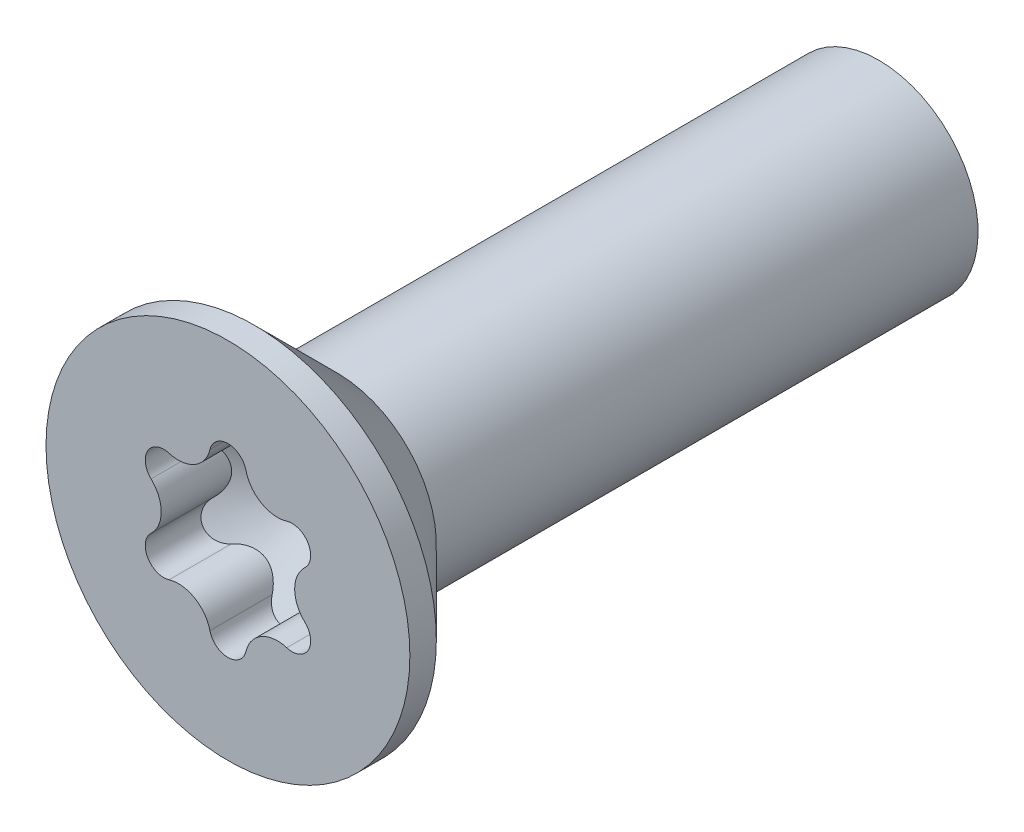
SolidWorks part; units mm, degrees
ref_plane "Front Plane" through (0, 0, 0) normal (0, 0, 1) x (1, 0, 0)
ref_plane "Top Plane" through (0, 0, 0) normal (0, 1, 0) x (1, 0, 0)
ref_plane "Right Plane" through (0, 0, 0) normal (1, 0, 0) x (0, 0, -1)
other "Configuration Table"
sketch "BodySke" plane through (0, 0, 0) normal (1, 0, 0) x (0, 0, -1)
  line L0 (0, 0) -> (-1787.2758, 0) construction
  line L1 (0, 0) -> (0, 2.75)
  line L2 (0.4, 2.75) -> (1.65, 1.5)
  line L3 (0.4, -2.75) -> (1.65, -1.5) construction
  line L4 (1.65, 1.5) -> (10, 1.5)
  line L5 (10, 1.5) -> (10, 0)
  line L6 (10, 0) -> (0, 0)
  line L7 (0, 0) -> (0, 50000) construction
  line L8 (0.4, 2.75) -> (0, 2.75)
  dimension "D" = 3
  dimension "Dk" = 5.5
  dimension "K" = 1.65
  dimension "L" = 10
  dimension "D1" = 90
  dimension "B" = 10
revolve "Base-Revolve" add sketch "BodySke" angle 360 about L0
cosmetic thread "ThreadCosmetic" [suppressed] parameters "ThdLen"=8.35, "MinorDia"=2.439
sketch "PreBSke" plane through (0, 0, 0) normal (1, 0, 0) x (0, 0, -1)
  line L0 (0, 0) -> (-50000, 0) construction
  line L1 (0, 0) -> (0, 1.4)
  line L2 (0, 3.15) -> (0, -3.15) construction
  line L3 (0, 1.4) -> (0.83, 1.4)
  line L4 (0.83, 1.4) -> (1.6712, 0)
  line L5 (1.6712, 0) -> (0, 0)
  line L6 (0.83, -1.4) -> (1.6712, 0) construction
  dimension "T" = 0.83
  dimension "A" = 2.8
  dimension "D1" = 118
revolve "PreBroach" cut sketch "PreBSke" angle 360 about L0
sketch "HexSke" plane through (0, 0, 0) normal (0, 0, 1) x (1, 0, 0)
  line L0 (0, 0) -> (-43301.2702, 25000) construction
  line L1 (0, 0) -> (-43301.2702, -25000) construction
  line L2 (0, 0) -> (50000, 0) construction
  arc A0 (-1.1621, -0.3564) -> (-1.1621, 0.3564) centre (-1.4984, 0) ccw
  arc A1 (-1.2124, 0.7) -> (-1.1621, 0.3564) centre (-0.9699, 0.56) ccw
  arc A2 (-1.1621, -0.3564) -> (-1.2124, -0.7) centre (-0.9699, -0.56) ccw
  arc A3 (-0.8897, 0.8282) -> (-1.2124, 0.7) centre (-0.9699, 0.56) ccw
  circle A4 centre (0, 0) radius 1.0084 construction
  circle A5 centre (0, 0) radius 1.4 construction
  arc A6 (-0.8897, 0.8282) -> (-0.2724, 1.1846) centre (-0.7492, 1.2977) ccw
  arc A7 (0, 1.4) -> (-0.2724, 1.1846) centre (0, 1.12) ccw
  arc A8 (0.2724, 1.1846) -> (0, 1.4) centre (0, 1.12) ccw
  arc A9 (0.2724, 1.1846) -> (0.8897, 0.8282) centre (0.7492, 1.2977) ccw
  arc A10 (1.2124, 0.7) -> (0.8897, 0.8282) centre (0.9699, 0.56) ccw
  arc A11 (1.1621, 0.3564) -> (1.2124, 0.7) centre (0.9699, 0.56) ccw
  arc A12 (1.1621, 0.3564) -> (1.1621, -0.3564) centre (1.4984, 0) ccw
  arc A13 (1.2124, -0.7) -> (1.1621, -0.3564) centre (0.9699, -0.56) ccw
  arc A14 (0.8897, -0.8282) -> (1.2124, -0.7) centre (0.9699, -0.56) ccw
  arc A15 (0.8897, -0.8282) -> (0.2724, -1.1846) centre (0.7492, -1.2977) ccw
  arc A16 (0, -1.4) -> (0.2724, -1.1846) centre (0, -1.12) ccw
  arc A17 (-0.2724, -1.1846) -> (0, -1.4) centre (0, -1.12) ccw
  arc A18 (-0.2724, -1.1846) -> (-0.8897, -0.8282) centre (-0.7492, -1.2977) ccw
  arc A19 (-1.2124, -0.7) -> (-0.8897, -0.8282) centre (-0.9699, -0.56) ccw
  circle A20 centre (0, 0) radius 1.4 construction
  circle A21 centre (0, 0) radius 1.4
  point P56 (0, 0)
  circle M6 centre (0, 0) radius 1.4
  dimension "B" = 2.0169
  dimension "Ri" = 0.28
  dimension "Re" = 0.49
  dimension "D1" = 60
  dimension "D5" = 6
extrude "Hexalobular" add sketch "HexSke" against normal up to next contours A2 A0 A1 M6 | A7 A3 A6 M6 | A10 A8 A9 M6 | A13 A11 A12 M6 | A16 A14 A15 M6 | A19 A17 A18 M6
sketch "ThdSchSke" plane through (0, 0, 0) normal (1, 0, 0) x (0, 0, -1)
  line L0 (10.1619, 1.5) -> (10, 1.2195)
  line L1 (10, 1.2195) -> (9.8381, 1.5)
  line L2 (9.8381, 1.5) -> (10.1619, 1.5)
  line L3 (10, 1.2195) -> (10, 1.5) construction
  line L4 (10, -1.5) -> (10, 1.5) construction
  line L5 (10, 1.5) -> (1.65, 1.5) construction
  line L6 (0, 0) -> (-50000, 0) construction
  dimension "MinorDia" = 2.439
  dimension "D1" = 60
  dimension "D2" = 0.3239
revolve "ThreadSchematic" cut sketch "ThdSchSke" angle 360 about L6
ref_plane "ThreadPlane" through (0, 0, -1.65) normal (0, 0, -1) x (-1, 0, 0)
pattern_linear "ThdSchPat" [suppressed] count 11
equation "\"MinorDia@ThreadCosmetic\" = \"MinorDia@ThdSchSke\""
equation "\"ThdLen@ThreadCosmetic\" = \"ThreadLength\""
equation "\"Ri@HexSke\"= .1 * \"A@PreBSke\""
equation "\"Re@HexSke\"= .175 * \"A@PreBSke\""
equation "\"ThreadLength\"= IIF ( \"B@BodySke\" = \"L@BodySke\" , \"L@BodySke\" - \"K@BodySke\" , \"B@BodySke\" )"
equation "\"ThdLen@ThreadPlane\"=\"ThreadLength\""
